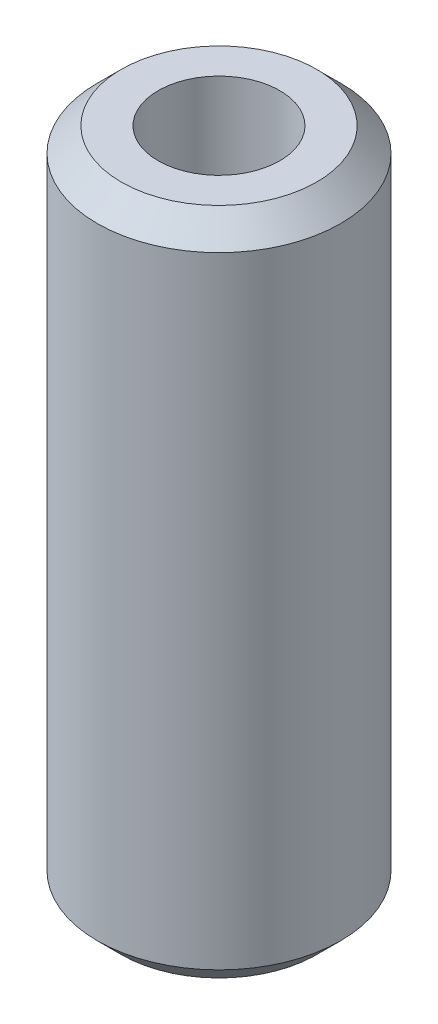
SolidWorks part; units mm, degrees
ref_plane "Plan de face" through (0, 0, 0) normal (0, 0, 1) x (1, 0, 0)
ref_plane "Plan de dessus" through (0, 0, 0) normal (0, 1, 0) x (1, 0, 0)
ref_plane "Plan de droite" through (0, 0, 0) normal (1, 0, 0) x (0, 0, -1)
sketch "Esquisse1" plane through (0, 0, 0) normal (0, 1, 0) x (1, 0, 0)
  circle A0 centre (0, 0) radius 6.35
  circle A1 centre (0, 0) radius 12.7
  dimension "D1" = 12.7
  dimension "D2" = 25.4
extrude "Boss.-Extru.1" add sketch "Esquisse1" along normal mid plane 69.85
chamfer "Chanfrein1" distance 2.5 angle 45 2 edges at (0, -34.925, 12.7) (0, 34.925, 12.7)
